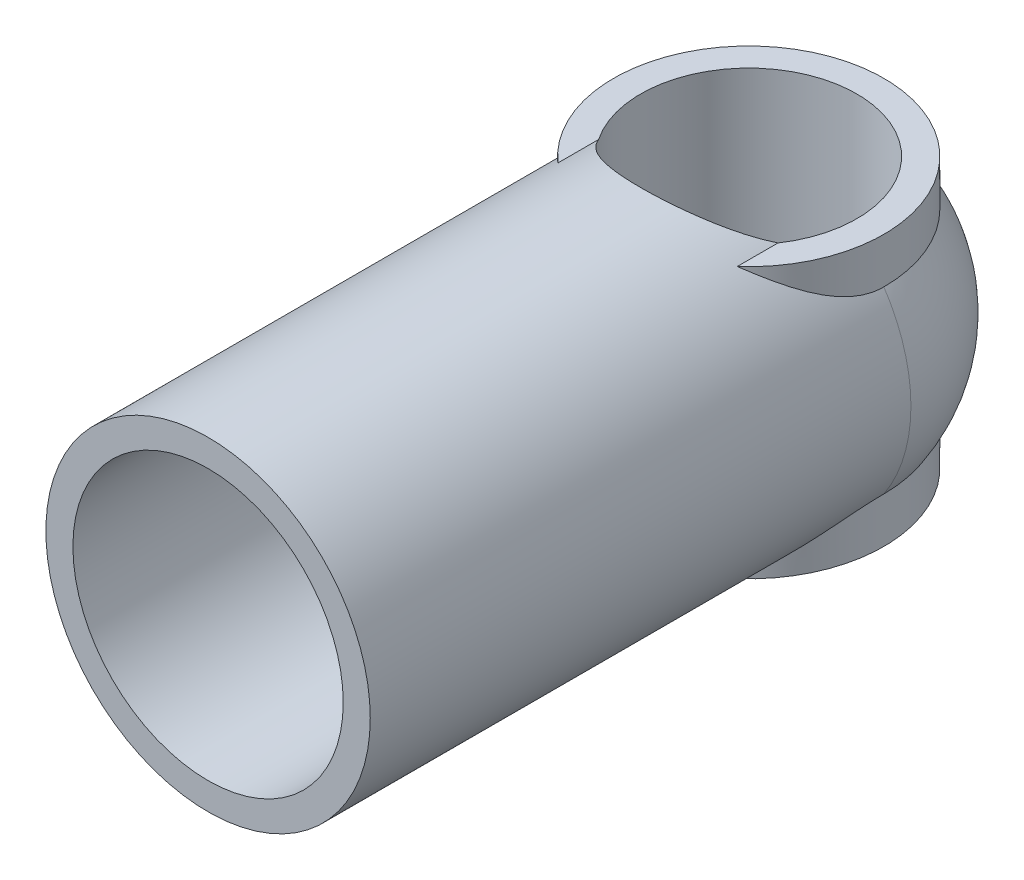
SolidWorks part; units mm, degrees
material "6061 合金"
ref_plane "前视基准面" through (0, 0, 0) normal (0, 0, 1) x (1, 0, 0)
ref_plane "上视基准面" through (0, 0, 0) normal (0, 1, 0) x (1, 0, 0)
ref_plane "右视基准面" through (0, 0, 0) normal (1, 0, 0) x (0, 0, -1)
sketch "草图1" plane through (0, 0, 0) normal (0, 0, 1) x (1, 0, 0)
  circle A0 centre (0, 0) radius 10
  circle A1 centre (0, 0) radius 12
  dimension "D1" = 20
  dimension "D2" = 2
extrude "凸台-拉伸1" add sketch "草图1" along normal blind 40
sketch "草图2" plane through (0, 0, 0) normal (0, 1, 0) x (1, 0, 0)
  line L0 (-12, 0) -> (-10, 0)
  line L1 (0, 12) -> (0, 10)
  line L2 (0, 10) -> (0, 0) construction
  arc A0 (0, 12) -> (-12, 0) centre (0, 0) ccw
  arc A1 (0, 10) -> (-10, 0) centre (0, 0) ccw
revolve "旋转1" add sketch "草图2" angle 360 about L2
sketch "草图3" plane through (0, 0, 0) normal (0, 1, 0) x (1, 0, 0)
  circle A0 centre (0, 0) radius 8
  circle A1 centre (0, 0) radius 10
  dimension "D1" = 16
  dimension "D2" = 20
extrude "凸台-拉伸2" add sketch "草图3" along normal mid plane 20
sketch "草图4" plane through (0, 0, 0) normal (0, 1, 0) x (1, 0, 0)
  circle A0 centre (0, 0) radius 8
extrude "切除-拉伸1" cut sketch "草图4" against normal through all both and the other way through all
